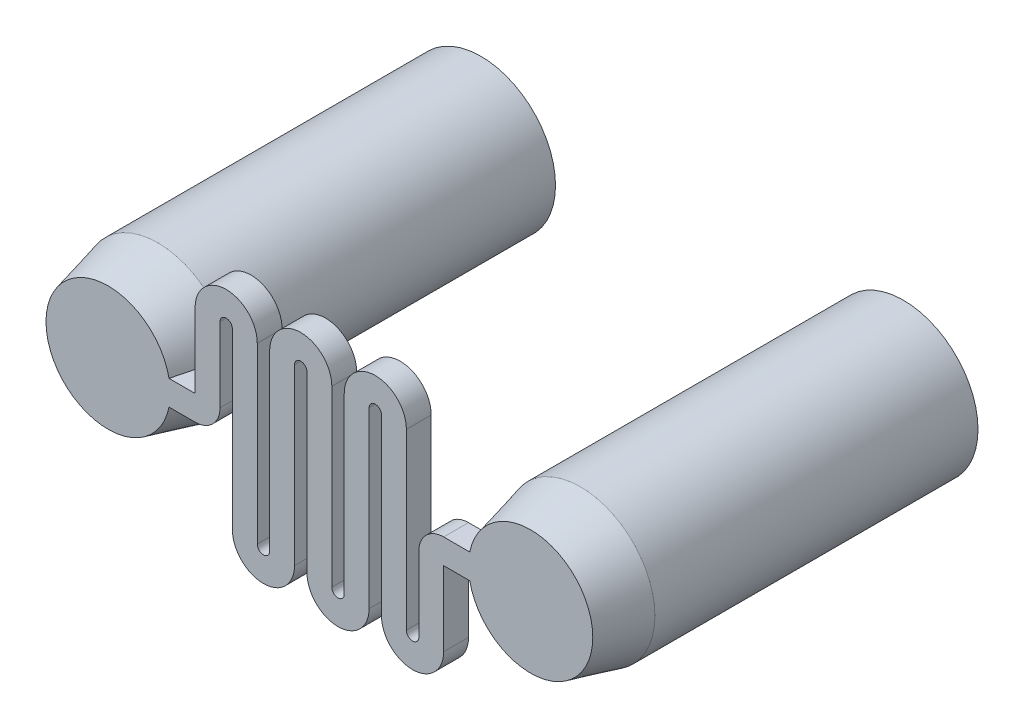
SolidWorks part; units mm, degrees
ref_plane "Front Plane" through (0, 0, 0) normal (0, 0, 1) x (1, 0, 0)
ref_plane "Top Plane" through (0, 0, 0) normal (0, 1, 0) x (1, 0, 0)
ref_plane "Right Plane" through (0, 0, 0) normal (1, 0, 0) x (0, 0, -1)
sketch "Sketch2" plane through (0, 0, 0) normal (0, 0, 1) x (1, 0, 0)
  line L3 (-20.5, -1) -> (-13.5, -1)
  line L6 (-11.5, 1) -> (-11.5, 7)
  line L9 (-10.5, 7) -> (-10.5, 0)
  line L12 (-10.5, 0) -> (-10.5, -7)
  line L15 (-5.5, -7) -> (-5.5, 0)
  line L18 (-5.5, 0) -> (-5.5, 7)
  line L21 (-4.5, 7) -> (-4.5, 0)
  line L22 (-4.5, 0) -> (-4.5, -7)
  line L23 (0.5, -7) -> (0.5, 0)
  line L24 (0.5, 0) -> (0.5, 7)
  line L25 (1.5, 7) -> (1.5, 0)
  line L26 (1.5, 0) -> (1.5, -7)
  line L27 (6.5, -7) -> (6.5, -1)
  line L28 (6.5, -1) -> (13.5, -1)
  line L29 (-20.5, 1) -> (-13.5, 1)
  line L30 (-13.5, 1) -> (-13.5, 7)
  line L31 (-8.5, 7) -> (-8.5, 0)
  line L32 (-8.5, 0) -> (-8.5, -7)
  line L33 (-7.5, -7) -> (-7.5, 0)
  line L34 (-7.5, 0) -> (-7.5, 7)
  line L35 (-2.5, 7) -> (-2.5, 0)
  line L36 (-2.5, 0) -> (-2.5, -7)
  line L37 (-1.5, -7) -> (-1.5, 0)
  line L38 (-1.5, 0) -> (-1.5, 7)
  line L39 (3.5, 7) -> (3.5, 0)
  line L40 (3.5, 0) -> (3.5, -7)
  line L41 (4.5, -7) -> (4.5, -1)
  line L42 (6.5, 1) -> (13.5, 1)
  arc A8 (-11.5, 1) -> (-13.5, -1) centre (-13.5, 1) cw
  arc A9 (-11.5, 7) -> (-10.5, 7) centre (-11, 7) cw
  arc A10 (-10.5, -7) -> (-5.5, -7) centre (-8, -7) ccw
  arc A11 (-5.5, 7) -> (-4.5, 7) centre (-5, 7) cw
  arc A12 (-4.5, -7) -> (0.5, -7) centre (-2, -7) ccw
  arc A13 (0.5, 7) -> (1.5, 7) centre (1, 7) cw
  arc A14 (1.5, -7) -> (6.5, -7) centre (4, -7) ccw
  arc A17 (-13.5, 7) -> (-8.5, 7) centre (-11, 7) cw
  arc A18 (-8.5, -7) -> (-7.5, -7) centre (-8, -7) ccw
  arc A19 (-7.5, 7) -> (-2.5, 7) centre (-5, 7) cw
  arc A20 (-2.5, -7) -> (-1.5, -7) centre (-2, -7) ccw
  arc A21 (-1.5, 7) -> (3.5, 7) centre (1, 7) cw
  arc A22 (3.5, -7) -> (4.5, -7) centre (4, -7) ccw
  arc A23 (4.5, -1) -> (6.5, 1) centre (6.5, -1) cw
  arc A24 (-20.5, 1) -> (-20.5, -1) centre (-20.5, 0) ccw
  arc A25 (13.5, -1) -> (13.5, 1) centre (13.5, 0) ccw
  point P4 (0, 0)
  point P32 (5.5, 0)
  point P35 (-12.5, 0)
  dimension "D1" = 8
  dimension "D14" = 8
extrude "Boss-Extrude1" add sketch "Sketch2" along normal blind 2
ref_plane "Plane1" through (0, 0, 0) normal (0, 1, 0) x (1, 0, 0)
sketch "Sketch3" plane through (0, 0, 0) normal (0, 1, 0) x (1, 0, 0)
  line L0 (-20.5, -2) -> (-25.5, -2)
  line L2 (-20.5, -2) -> (-20.5, 28)
  line L3 (-20.5, 28) -> (-26.5, 28)
  line L4 (-26.5, 28) -> (-26.5, 2)
  line L5 (-26.5, 2) -> (-25.5, -2)
  dimension "D1" = 5
  dimension "D3" = 30
  dimension "D4" = 6
revolve "Revolve1" add sketch "Sketch3" angle 360 about L2
ref_plane "Plane2" through (0, 0, 0) normal (0, 1, 0) x (1, 0, 0)
sketch "Sketch4" plane through (0, 0, 0) normal (0, 1, 0) x (1, 0, 0)
  line L0 (13.5, -2) -> (18.5, -2)
  line L2 (13.5, -2) -> (13.5, 28)
  line L3 (13.5, 28) -> (19.5, 28)
  line L4 (19.5, 28) -> (19.5, 2)
  line L5 (19.5, 2) -> (18.5, -2)
  dimension "D1" = 5
  dimension "D3" = 30
  dimension "D4" = 6
revolve "Revolve2" add sketch "Sketch4" angle 360 about L2
sketch "Sketch5" plane through (0, 0, -28) normal (0, 0, -1) x (-1, 0, 0)
  circle A0 centre (-13.5, 0) radius 5
  circle A1 centre (20.5, 0) radius 5
  dimension "D1" = 10
  dimension "D2" = 10
extrude "Cut-Extrude1" cut sketch "Sketch5" against normal blind 28
